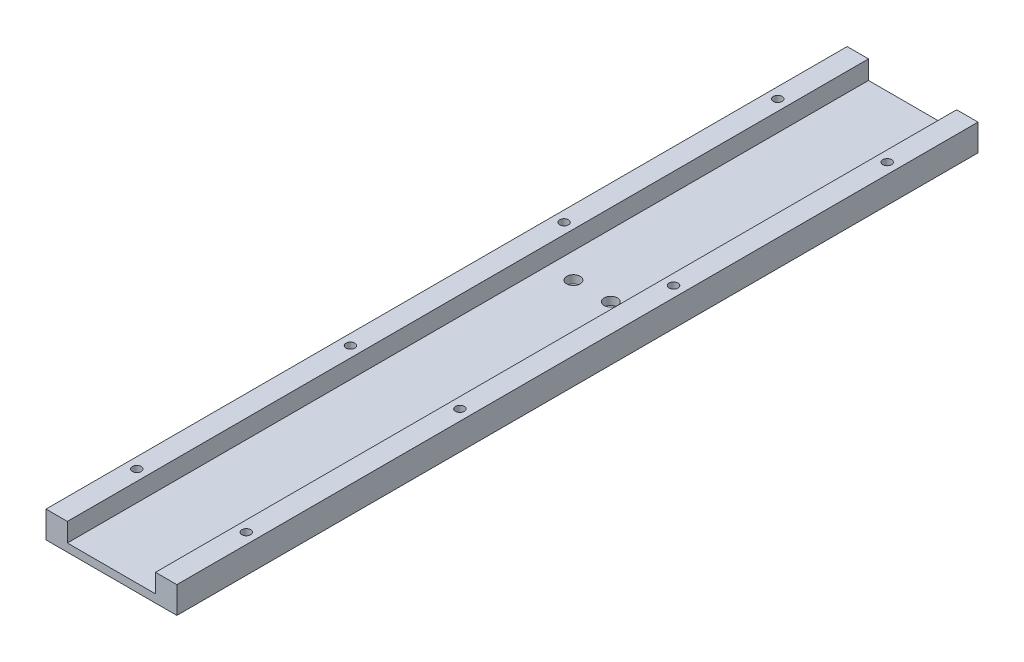
SolidWorks part; units mm, degrees
other "Objet de détail1"
ref_plane "Front" through (0, 0, 0) normal (0, 0, 1) x (1, 0, 0)
ref_plane "Top" through (0, 0, 0) normal (0, 1, 0) x (1, 0, 0)
ref_plane "Right" through (0, 0, 0) normal (1, 0, 0) x (0, 0, -1)
sketch "Esquisse1" plane through (0, 0, 0) normal (0, 0, 1) x (1, 0, 0)
  line L0 (0, 0) -> (0, 10)
  line L1 (0, 10) -> (8, 10)
  line L2 (49, 10) -> (41, 10)
  line L4 (8, 10) -> (8, 3)
  line L5 (8, 3) -> (41, 3)
  line L6 (0, 0) -> (49, 0)
  line L7 (24.5, 0) -> (24.5, 3) construction
  line L8 (41, 10) -> (41, 3)
  line L12 (49, 0) -> (49, 10)
  dimension "D1" = 33
  dimension "D2" = 3
  dimension "D3" = 8
  dimension "D4" = 10
extrude "Boss.-Extru.1" add sketch "Esquisse1" along normal blind 300
sketch "Esquisse2" plane through (0, 3, 0) normal (0, 1, 0) x (1, 0, 0)
  line L0 (24.5, -300) -> (24.5, -120) construction
  line L1 (41, -300) -> (8, -300) construction
  line L2 (24.5, -120) -> (17.5, -120) construction
  circle A0 centre (17.5, -120) radius 2.5
  circle A1 centre (31.5, -120) radius 2.5
  dimension "D1" = 5
  dimension "D2" = 14
  dimension "D3" = 180
extrude "Enlèv. mat.-Extru.1" cut sketch "Esquisse2" against normal through all both and the other way through all
sketch "Esquisse3" plane through (0, 10, 0) normal (0, 1, 0) x (1, 0, 0)
  line L0 (45, -300) -> (45, 0) construction
  line L1 (49, -300) -> (41, -300) construction
  line L2 (49, 0) -> (41, 0) construction
  line L3 (45, -150) -> (49, -150) construction
  line L4 (49, -300) -> (49, 0) construction
  line L5 (24.5, -300) -> (24.5, 0) construction
  line L6 (41, -300) -> (8, -300) construction
  line L7 (41, 0) -> (8, 0) construction
  line L8 (4, -150) -> (0, -150) construction
  circle A0 centre (45, -270) radius 1.65
  circle A1 centre (45, -190) radius 1.65
  circle A2 centre (45, -110) radius 1.65
  circle A3 centre (45, -30) radius 1.65
  circle A4 centre (4, -30) radius 1.65
  circle A5 centre (4, -110) radius 1.65
  circle A6 centre (4, -190) radius 1.65
  circle A7 centre (4, -270) radius 1.65
  dimension "D3" = 3.3
  dimension "D1" = 80
  dimension "D2" = 40
extrude "Enlèv. mat.-Extru.2" cut sketch "Esquisse3" against normal through all both and the other way through all
